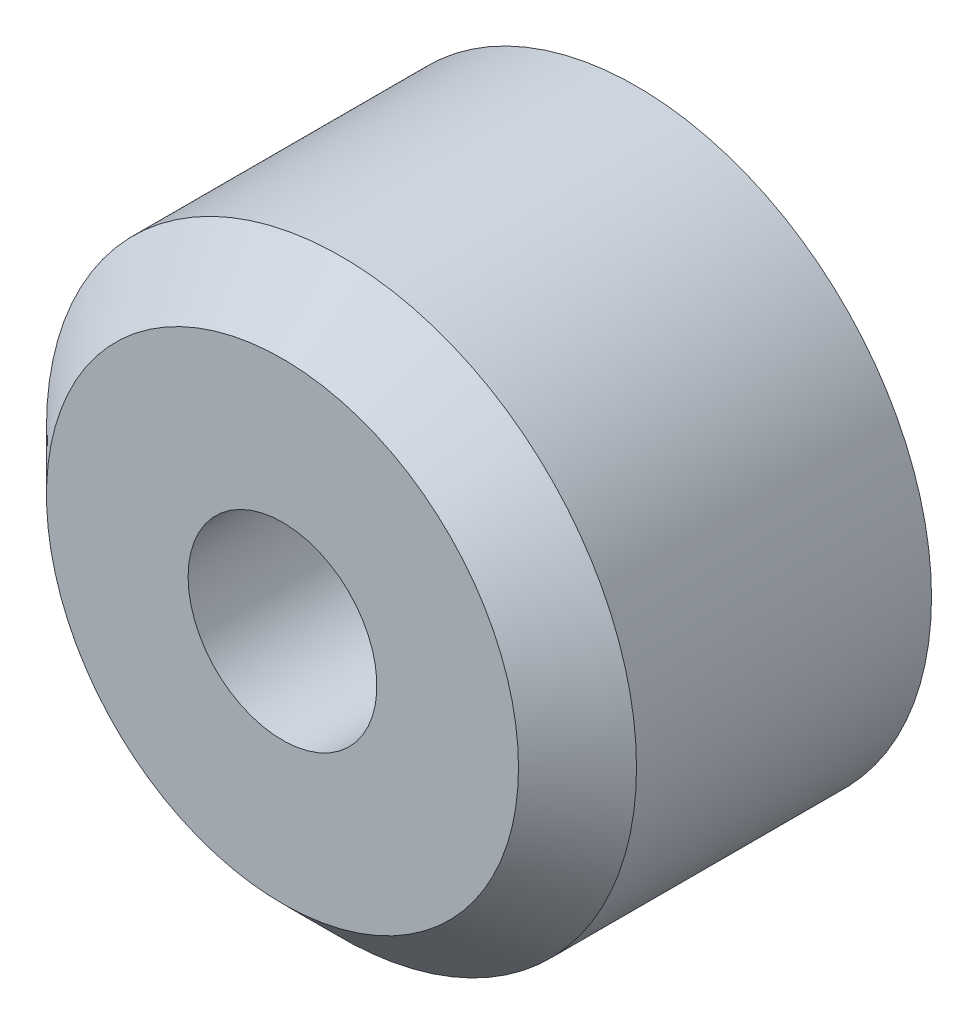
SolidWorks part; units mm, degrees
ref_plane "Front Plane" through (0, 0, 0) normal (0, 0, 1) x (1, 0, 0)
ref_plane "Top Plane" through (0, 0, 0) normal (0, 1, 0) x (1, 0, 0)
ref_plane "Right Plane" through (0, 0, 0) normal (1, 0, 0) x (0, 0, -1)
sketch "Sketch1" plane through (0, 0, 0) normal (0, 0, 1) x (1, 0, 0)
  circle A0 centre (0, 0) radius 5
  dimension "D1" = 10
extrude "Boss-Extrude1" add sketch "Sketch1" along normal blind 6
hole_wizard "CSK for M3 Flat Head Machine Screw1" positions "Sketch2" profile "Sketch3" countersink size "M3" standard "ANSI Metric" end condition through all
sketch "Sketch2" plane through (0, 0, 0) normal (0, 0, -1) x (-1, 0, 0)
  point P0 (0, 0)
sketch "Sketch3" plane through (0, 0, 0) normal (1, 0, 0) x (0, 1, 0)
  line L0 (0, 0) -> (0, 6)
  line L1 (0, 6) -> (1.6, 6)
  line L2 (1.6, 6) -> (1.6, 1.55)
  line L3 (1.6, 1.55) -> (3.15, 0)
  line L5 (3.15, 0) -> (0, 0)
  line L6 (-1.6, 1.55) -> (-3.15, 0) construction
  line L11 (0, -6.35) -> (0, 107.95) construction
  dimension "Thru Hole Dia." = 3.2
  dimension "Thru Hole Depth" = 6
  dimension "Near C'Sink Dia." = 6.3
  dimension "Near C'Sink Angle" = 90
chamfer "Chamfer1" distance 1 angle 45 1 edges at (5, 0, 6)
